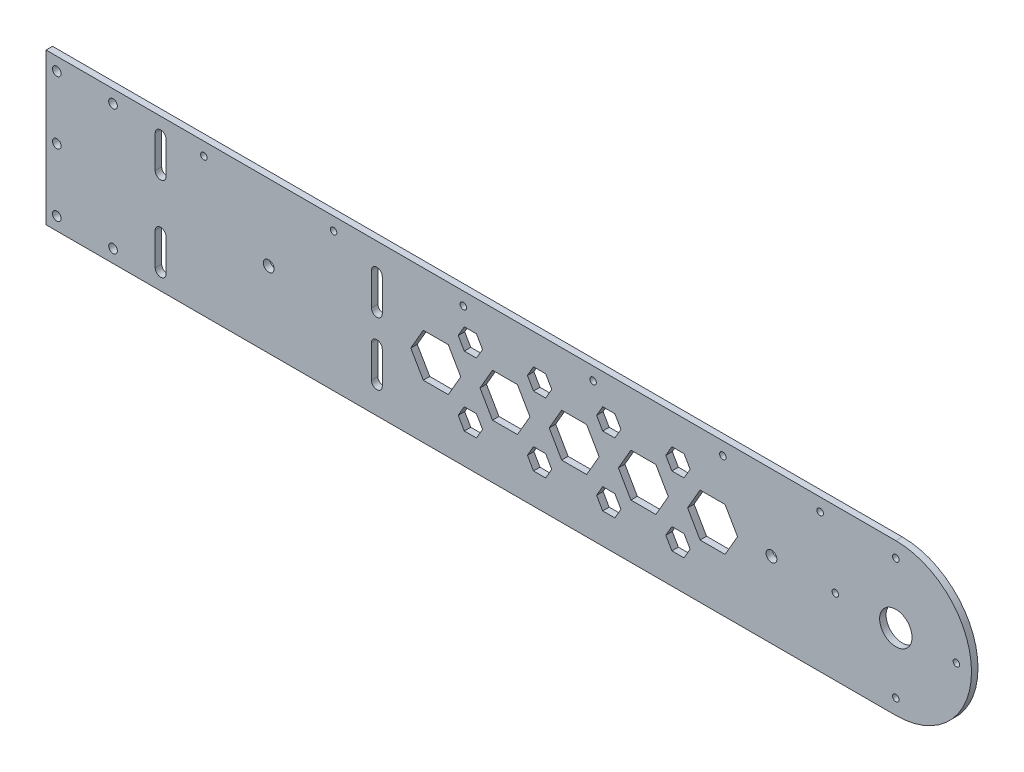
SolidWorks part; units mm, degrees
material "6061 Alloy"
ref_plane "Front Plane" through (0, 0, 0) normal (0, 0, 1) x (1, 0, 0)
ref_plane "Top Plane" through (0, 0, 0) normal (0, 1, 0) x (1, 0, 0)
ref_plane "Right Plane" through (0, 0, 0) normal (1, 0, 0) x (0, 0, -1)
sketch "Sketch1" plane through (0, 0, 0) normal (0, 0, 1) x (1, 0, 0)
  line L0 (0, 0) -> (45.8221, 0) construction
  line L1 (0, 35) -> (393, 35) construction
  line L2 (0, 35) -> (0, -35)
  line L3 (0, -35) -> (393, -35) construction
  line L5 (0, 35) -> (393, 35)
  line L6 (393, -35) -> (0, -35)
  circle A0 centre (5, 29) radius 2
  circle A2 centre (5, -29) radius 2
  circle A4 centre (393, 0) radius 7.5
  circle A7 centre (103, 0) radius 2.5
  circle A8 centre (31, 29) radius 2
  circle A9 centre (31, -29) radius 2
  circle A10 centre (5, 0) radius 2
  arc A11 (393, 35) -> (393, -35) centre (393, 0) cw
  point P0 (0, 0)
  point P8 (153, 0)
  point P14 (53, 0)
  point P16 (0, 0)
  dimension "D2" = 4
  dimension "D5" = 393
  dimension "D10" = 15
  dimension "D6" = 50
  dimension "D7" = 50
  dimension "D14" = 5
  dimension "D8" = 4
  dimension "D11" = 4
  dimension "D15" = 4
  dimension "D1" = 70
  dimension "D3" = 5
  dimension "D4" = 6
  dimension "D9" = 0
  dimension "D12" = 290
  dimension "D13" = 26
extrude "Boss-Extrude1" add sketch "Sketch1" along normal blind 3
sketch "Sketch3" plane through (0, 0, 3) normal (0, 0, 1) x (1, 0, 0)
  line L0 (53, 110.2799) -> (53, -110.2799)
  line L1 (153, 124.2968) -> (153, -124.2968)
  circle A0 centre (103, 0) radius 2.5 construction
  point P3 (53, 0)
  point P6 (153, 0)
  dimension "D1" = 50
  dimension "D2" = 50
split line "Split Line1" [suppressed]
sketch "Sketch4" plane through (0, 0, 3) normal (0, 0, 1) x (1, 0, 0)
  line L0 (53, 27) -> (53, 12) construction
  line L1 (55.5, 27) -> (55.5, 12)
  line L2 (50.5, 27) -> (50.5, 12)
  line L3 (153, 22) -> (153, 7) construction
  line L4 (155.5, 22) -> (155.5, 7)
  line L5 (150.5, 22) -> (150.5, 7)
  line L6 (53, 0) -> (153, 0) construction
  line L7 (153, -22) -> (153, -7) construction
  line L8 (155.5, -22) -> (155.5, -7)
  line L9 (150.5, -22) -> (150.5, -7)
  line L10 (53, -27) -> (53, -12) construction
  line L11 (55.5, -27) -> (55.5, -12)
  line L12 (50.5, -27) -> (50.5, -12)
  arc A0 (55.5, 27) -> (50.5, 27) centre (53, 27) ccw
  arc A1 (50.5, 12) -> (55.5, 12) centre (53, 12) ccw
  arc A2 (155.5, 22) -> (150.5, 22) centre (153, 22) ccw
  arc A3 (150.5, 7) -> (155.5, 7) centre (153, 7) ccw
  circle A4 centre (103, 0) radius 2.5 construction
  arc A5 (155.5, -22) -> (150.5, -22) centre (153, -22) cw
  arc A6 (150.5, -7) -> (155.5, -7) centre (153, -7) cw
  arc A7 (55.5, -27) -> (50.5, -27) centre (53, -27) cw
  arc A8 (50.5, -12) -> (55.5, -12) centre (53, -12) cw
  point P2 (53, 19.5)
  point P8 (153, 14.5)
  point P23 (153, -14.5)
  point P30 (53, -19.5)
  dimension "D1" = 2.5
  dimension "D2" = 2.5
  dimension "D4" = 50
  dimension "D3" = 50
  dimension "D5" = 22
  dimension "D6" = 12
  dimension "D7" = 27
  dimension "D8" = 7
extrude "Cut-Extrude1" cut sketch "Sketch4" against normal through all both and the other way through all
sketch "Sketch5" plane through (0, 0, 3) normal (0, 0, 1) x (1, 0, 0)
  line L0 (284.5811, 0) -> (386.4189, 0) construction
  circle A2 centre (335.5, 0) radius 2.5
  circle A3 centre (103, 0) radius 2.5 construction
  dimension "D1" = 5
  dimension "D2" = 232.5
extrude "Cut-Extrude2" cut sketch "Sketch5" against normal through all both and the other way through all
sketch "Sketch6" plane through (0, 0, 3) normal (0, 0, 1) x (1, 0, 0)
  circle A4 centre (421, 0) radius 1.5
  circle A5 centre (393, -28) radius 1.5
  circle A6 centre (393, 28) radius 1.5
  circle A7 centre (393, 0) radius 7.5 construction
  circle A8 centre (365, 0) radius 1.5
  point P13 (393, 0)
  dimension "D1" = 3
  dimension "D2" = 0
  dimension "D3" = 28
extrude "Cut-Extrude3" cut sketch "Sketch6" against normal through all both and the other way through all
sketch "Sketch7" plane through (0, 0, 3) normal (0, 0, 1) x (1, 0, 0)
  line L0 (393, 35) -> (0, 35) construction
  line L1 (73, 29) -> (133, 29) construction
  line L2 (0, 0) -> (393, 0) construction
  circle A0 centre (73, 29) radius 1.5
  circle A2 centre (133, 29) radius 1.5
  circle A3 centre (193, 29) radius 1.5
  circle A4 centre (253, 29) radius 1.5
  circle A5 centre (313, 29) radius 1.5
  circle A12 centre (358, 29) radius 1.5
  circle A13 centre (103, 0) radius 2.5 construction
  dimension "D1" = 3
  dimension "D6" = 3
  dimension "D3" = 30
  dimension "D2" = 6
  dimension "D5" = 60
  dimension "D7" = 45
  dimension "D4" = 5
extrude "Cut-Extrude4" cut sketch "Sketch7" against normal blind 3
sketch "Sketch8" plane through (0, 0, 3) normal (0, 0, 1) x (1, 0, 0)
  line L0 (164.5554, 0) -> (302.378, 0) construction
  line L1 (223.795, 0) -> (218.0215, 10)
  line L2 (191.795, 0) -> (186.0215, 10)
  line L3 (186.0215, 10) -> (174.4745, 10)
  line L4 (174.4745, 10) -> (168.701, 0)
  line L5 (168.701, 0) -> (174.4745, -10)
  line L6 (174.4745, -10) -> (186.0215, -10)
  line L7 (186.0215, -10) -> (191.795, 0)
  line L8 (218.0215, 10) -> (206.4745, 10)
  line L9 (206.4745, 10) -> (200.701, 0)
  line L10 (200.701, 0) -> (206.4745, -10)
  line L11 (206.4745, -10) -> (218.0215, -10)
  line L12 (218.0215, -10) -> (223.795, 0)
  line L13 (255.795, 0) -> (250.0215, 10)
  line L14 (250.0215, 10) -> (238.4745, 10)
  line L15 (238.4745, 10) -> (232.701, 0)
  line L16 (232.701, 0) -> (238.4745, -10)
  line L17 (238.4745, -10) -> (250.0215, -10)
  line L18 (250.0215, -10) -> (255.795, 0)
  line L19 (287.795, 0) -> (282.0215, 10)
  line L20 (282.0215, 10) -> (270.4745, 10)
  line L21 (270.4745, 10) -> (264.701, 0)
  line L22 (264.701, 0) -> (270.4745, -10)
  line L23 (270.4745, -10) -> (282.0215, -10)
  line L24 (282.0215, -10) -> (287.795, 0)
  line L25 (191.795, 0) -> (223.795, 0) construction
  line L26 (233.8658, 16) -> (231.0569, 20.8651)
  line L27 (201.8658, 16) -> (199.0569, 20.8651)
  line L28 (199.0569, 20.8651) -> (193.4391, 20.8651)
  line L29 (193.4391, 20.8651) -> (190.6302, 16)
  line L30 (190.6302, 16) -> (193.4391, 11.1349)
  line L31 (193.4391, 11.1349) -> (199.0569, 11.1349)
  line L32 (199.0569, 11.1349) -> (201.8658, 16)
  line L33 (231.0569, 20.8651) -> (225.4391, 20.8651)
  line L34 (225.4391, 20.8651) -> (222.6302, 16)
  line L35 (222.6302, 16) -> (225.4391, 11.1349)
  line L36 (225.4391, 11.1349) -> (231.0569, 11.1349)
  line L37 (231.0569, 11.1349) -> (233.8658, 16)
  line L38 (265.8658, 16) -> (263.0569, 20.8651)
  line L39 (263.0569, 20.8651) -> (257.4391, 20.8651)
  line L40 (257.4391, 20.8651) -> (254.6302, 16)
  line L41 (254.6302, 16) -> (257.4391, 11.1349)
  line L42 (257.4391, 11.1349) -> (263.0569, 11.1349)
  line L43 (263.0569, 11.1349) -> (265.8658, 16)
  line L44 (201.8658, 16) -> (233.8658, 16) construction
  line L63 (319.795, 0) -> (314.0215, 10)
  line L64 (314.0215, 10) -> (302.4745, 10)
  line L65 (302.4745, 10) -> (296.701, 0)
  line L66 (296.701, 0) -> (302.4745, -10)
  line L67 (302.4745, -10) -> (314.0215, -10)
  line L68 (314.0215, -10) -> (319.795, 0)
  line L69 (297.8658, 16) -> (295.0569, 20.8651)
  line L70 (295.0569, 20.8651) -> (289.4391, 20.8651)
  line L71 (289.4391, 20.8651) -> (286.6302, 16)
  line L72 (286.6302, 16) -> (289.4391, 11.1349)
  line L73 (289.4391, 11.1349) -> (295.0569, 11.1349)
  line L74 (295.0569, 11.1349) -> (297.8658, 16)
  line L75 (295.0569, -11.1349) -> (297.8658, -16)
  line L76 (289.4391, -11.1349) -> (295.0569, -11.1349)
  line L77 (286.6302, -16) -> (289.4391, -11.1349)
  line L78 (289.4391, -20.8651) -> (286.6302, -16)
  line L79 (295.0569, -20.8651) -> (289.4391, -20.8651)
  line L80 (297.8658, -16) -> (295.0569, -20.8651)
  line L81 (263.0569, -11.1349) -> (265.8658, -16)
  line L82 (257.4391, -11.1349) -> (263.0569, -11.1349)
  line L83 (254.6302, -16) -> (257.4391, -11.1349)
  line L84 (257.4391, -20.8651) -> (254.6302, -16)
  line L85 (263.0569, -20.8651) -> (257.4391, -20.8651)
  line L86 (265.8658, -16) -> (263.0569, -20.8651)
  line L87 (231.0569, -11.1349) -> (233.8658, -16)
  line L88 (225.4391, -11.1349) -> (231.0569, -11.1349)
  line L89 (222.6302, -16) -> (225.4391, -11.1349)
  line L90 (225.4391, -20.8651) -> (222.6302, -16)
  line L91 (231.0569, -20.8651) -> (225.4391, -20.8651)
  line L92 (233.8658, -16) -> (231.0569, -20.8651)
  line L93 (199.0569, -11.1349) -> (201.8658, -16)
  line L94 (193.4391, -11.1349) -> (199.0569, -11.1349)
  line L95 (190.6302, -16) -> (193.4391, -11.1349)
  line L96 (193.4391, -20.8651) -> (190.6302, -16)
  line L97 (199.0569, -20.8651) -> (193.4391, -20.8651)
  line L98 (201.8658, -16) -> (199.0569, -20.8651)
  circle A0 centre (180.248, 0) radius 10 construction
  circle A1 centre (196.248, 16) radius 4.8651 construction
  circle A3 centre (335.5, 0) radius 2.5 construction
  dimension "D7" = 15.705
  dimension "D1" = 5
  dimension "D2" = 32
  dimension "D3" = 20
  dimension "D5" = 32
  dimension "D6" = 16
  dimension "D8" = 16
  dimension "D4" = 4
extrude "Cut-Extrude5" cut sketch "Sketch8" against normal through all
